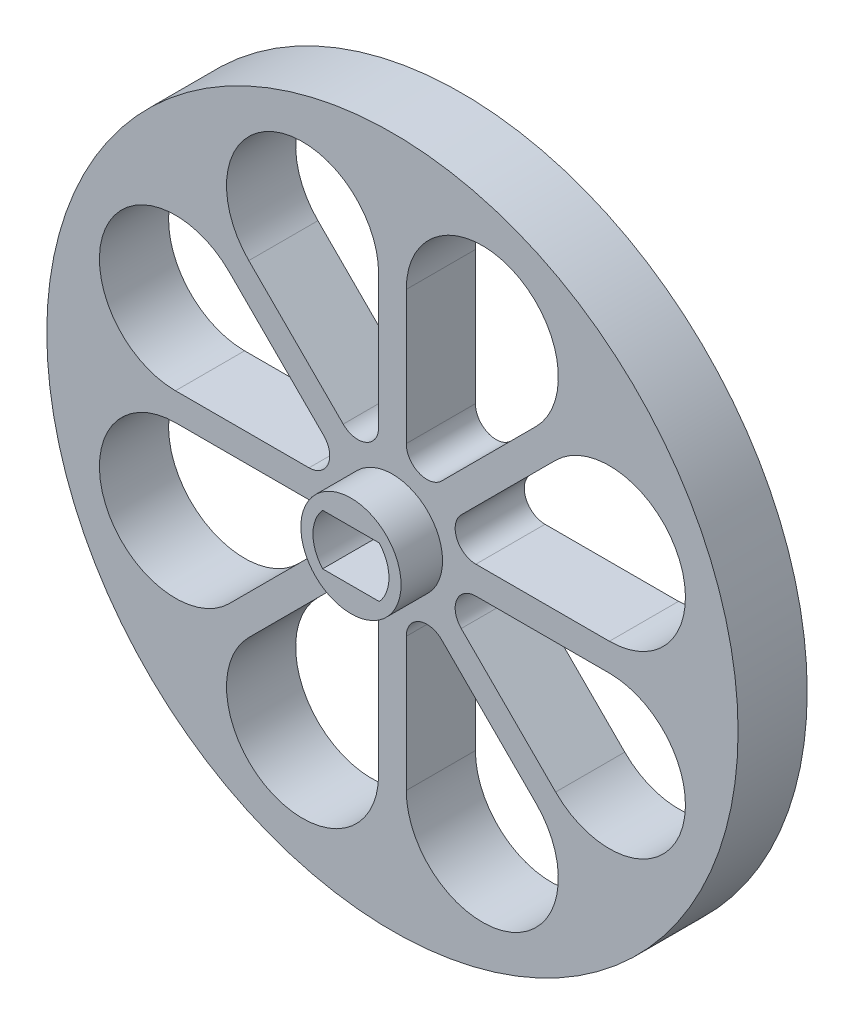
SolidWorks part; units mm, degrees
ref_plane "Front Plane" through (0, 0, 0) normal (0, 0, 1) x (1, 0, 0)
ref_plane "Top Plane" through (0, 0, 0) normal (0, 1, 0) x (1, 0, 0)
ref_plane "Right Plane" through (0, 0, 0) normal (1, 0, 0) x (0, 0, -1)
sketch "Sketch1" plane through (0, 0, 0) normal (0, 1, 0) x (1, 0, 0)
  line L0 (24.69, 90.8) -> (-0.31, 90.8)
  line L1 (-0.31, 90.8) -> (-0.31, 85.8)
  line L2 (-0.31, 85.8) -> (24.69, 85.8)
  line L3 (24.69, 85.8) -> (24.69, 90.8)
  line L4 (-0.31, 90.8) -> (-0.31, 85.8) construction
revolve "Revolve1" add sketch "Sketch1" angle 360 about L4
sketch "Sketch2" plane through (0, 0, -85.8) normal (0, 0, 1) x (1, 0, 0)
  circle A0 centre (-0.31, 0) radius 3.625
extrude "Boss-Extrude1" add sketch "Sketch2" along normal blind 3
sketch "Sketch3" plane through (0, 0, -90.8) normal (0, 0, -1) x (-1, 0, 0)
  line L0 (-1.739, -1.8342) -> (2.359, -1.8342)
  line L1 (2.359, 1.8342) -> (-1.739, 1.8342)
  arc A0 (-1.739, 1.8342) -> (-1.739, -1.8342) centre (0.31, 0) ccw
  arc A1 (2.359, -1.8342) -> (2.359, 1.8342) centre (0.31, 0) ccw
extrude "Cut-Extrude1" cut sketch "Sketch3" against normal through all
sketch "Sketch4" plane through (0, 0, -85.8) normal (0, 0, 1) x (1, 0, 0)
  line L0 (5.7255, 1) -> (15.3824, 1)
  line L1 (11.4933, 10.3891) -> (4.6649, 3.5607)
  arc A0 (15.3824, 1) -> (11.4933, 10.3891) centre (15.3824, 6.5) ccw
  arc A1 (4.6649, 3.5607) -> (5.7255, 1) centre (5.7255, 2.5) ccw
extrude "Cut-Extrude2" cut sketch "Sketch4" against normal through all
sketch "Sketch5" plane through (0, 0, -85.8) normal (0, 0, 1) x (1, 0, 0)
  line L0 (-12.1133, -10.3891) -> (-5.2849, -3.5607)
  line L1 (-6.3455, -1) -> (-16.0024, -1)
  arc A0 (-5.2849, -3.5607) -> (-6.3455, -1) centre (-6.3455, -2.5) ccw
  arc A1 (-16.0024, -1) -> (-12.1133, -10.3891) centre (-16.0024, -6.5) ccw
extrude "Cut-Extrude3" cut sketch "Sketch5" against normal through all
sketch "Sketch6" plane through (0, 0, -85.8) normal (0, 0, 1) x (1, 0, 0)
  line L0 (3.2507, 4.9749) -> (10.0791, 11.8033)
  line L1 (0.69, 15.6924) -> (0.69, 6.0355)
  arc A0 (0.69, 6.0355) -> (3.2507, 4.9749) centre (2.19, 6.0355) ccw
  arc A1 (10.0791, 11.8033) -> (0.69, 15.6924) centre (6.19, 15.6924) ccw
extrude "Cut-Extrude4" cut sketch "Sketch6" against normal through all
sketch "Sketch7" plane through (0, 0, -85.8) normal (0, 0, 1) x (1, 0, 0)
  line L0 (-3.8707, -4.9749) -> (-10.6991, -11.8033)
  line L1 (-1.31, -15.6924) -> (-1.31, -6.0355)
  arc A0 (-1.31, -6.0355) -> (-3.8707, -4.9749) centre (-2.81, -6.0355) ccw
  arc A1 (-10.6991, -11.8033) -> (-1.31, -15.6924) centre (-6.81, -15.6924) ccw
extrude "Cut-Extrude5" cut sketch "Sketch7" against normal through all
sketch "Sketch8" plane through (0, 0, -85.8) normal (0, 0, 1) x (1, 0, 0)
  line L0 (15.3824, -1) -> (5.7255, -1)
  line L1 (4.6649, -3.5607) -> (11.4933, -10.3891)
  arc A0 (5.7255, -1) -> (4.6649, -3.5607) centre (5.7255, -2.5) ccw
  arc A1 (11.4933, -10.3891) -> (15.3824, -1) centre (15.3824, -6.5) ccw
extrude "Cut-Extrude6" cut sketch "Sketch8" against normal through all
sketch "Sketch9" plane through (0, 0, -85.8) normal (0, 0, 1) x (1, 0, 0)
  line L0 (-16.0024, 1) -> (-6.3455, 1)
  line L1 (-5.2849, 3.5607) -> (-12.1133, 10.3891)
  arc A0 (-6.3455, 1) -> (-5.2849, 3.5607) centre (-6.3455, 2.5) ccw
  arc A1 (-12.1133, 10.3891) -> (-16.0024, 1) centre (-16.0024, 6.5) ccw
extrude "Cut-Extrude7" cut sketch "Sketch9" against normal through all
sketch "Sketch10" plane through (0, 0, -85.8) normal (0, 0, 1) x (1, 0, 0)
  line L0 (-1.31, 6.0355) -> (-1.31, 15.6924)
  line L1 (-10.6991, 11.8033) -> (-3.8707, 4.9749)
  arc A0 (-1.31, 15.6924) -> (-10.6991, 11.8033) centre (-6.81, 15.6924) ccw
  arc A1 (-3.8707, 4.9749) -> (-1.31, 6.0355) centre (-2.81, 6.0355) ccw
extrude "Cut-Extrude8" cut sketch "Sketch10" against normal through all
sketch "Sketch11" plane through (0, 0, -90.8) normal (0, 0, -1) x (-1, 0, 0)
  line L0 (-0.69, -15.6924) -> (-0.69, -6.0355)
  line L1 (-3.2507, -4.9749) -> (-10.0791, -11.8033)
  arc A0 (-10.0791, -11.8033) -> (-0.69, -15.6924) centre (-6.19, -15.6924) ccw
  arc A1 (-0.69, -6.0355) -> (-3.2507, -4.9749) centre (-2.19, -6.0355) ccw
extrude "Cut-Extrude9" cut sketch "Sketch11" against normal through all
